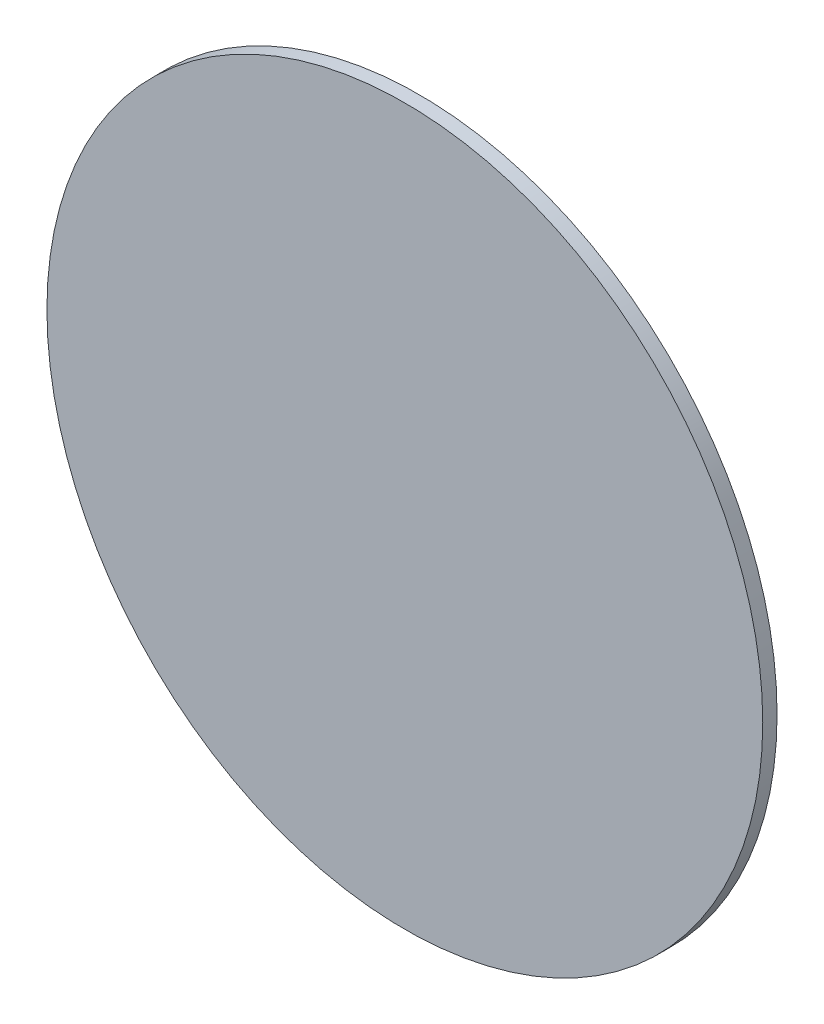
SolidWorks part; units mm, degrees
ref_plane "Front Plane" through (0, 0, 0) normal (0, 0, 1) x (1, 0, 0)
ref_plane "Top Plane" through (0, 0, 0) normal (0, 1, 0) x (1, 0, 0)
ref_plane "Right Plane" through (0, 0, 0) normal (1, 0, 0) x (0, 0, -1)
sketch "Baseplate" plane through (0, 0, 0) normal (0, 0, 1) x (1, 0, 0)
  circle A0 centre (0, 0) radius 500
extrude "Boss-Extrude1" add sketch "Baseplate" along normal blind 20
